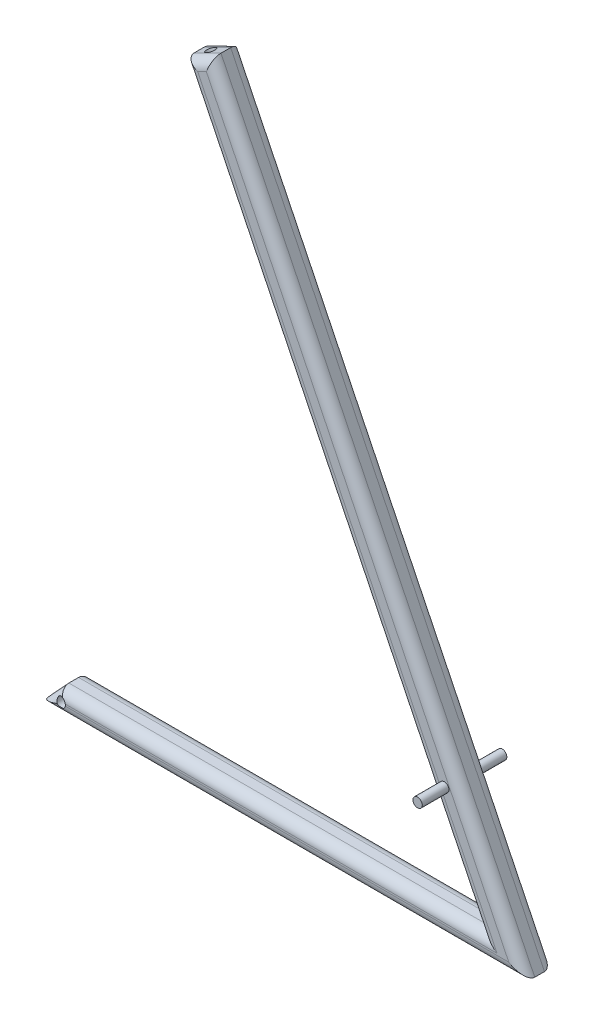
SolidWorks part; units mm, degrees
material "AA356.0-F"
ref_plane "Front Plane" through (0, 0, 0) normal (0, 0, 1) x (1, 0, 0)
ref_plane "Top Plane" through (0, 0, 0) normal (0, 1, 0) x (1, 0, 0)
ref_plane "Right Plane" through (0, 0, 0) normal (1, 0, 0) x (0, 0, -1)
sketch "Sketch1" plane through (0, 0, 0) normal (0, 0, 1) x (1, 0, 0)
  line L6 (-253.5187, -141.5797) -> (475.1092, -141.5797)
  line L7 (475.1092, -141.5797) -> (4.6879, 822.9269)
  line L8 (4.6879, 822.9269) -> (-35.3085, 803.4194)
  line L9 (-35.3085, 803.4194) -> (409.6382, -108.8566)
  line L10 (409.6382, -108.8566) -> (-223.3618, -108.8566)
  line L11 (-223.3618, -108.8566) -> (-253.5187, -141.5797)
  dimension "D1" = 64
  dimension "D2" = 728.6279
  dimension "D3" = 44.5
  dimension "D4" = 1015
  dimension "D5" = 633
  dimension "D6" = 44.5
extrude "Boss-Extrude1" add sketch "Sketch1" along normal blind 44.5
fillet "Fillet2" radius 15 12 edges at (93.1382, -108.8566, 44.5) (187.1649, 347.2814, 44.5) (-15.3103, 813.1732, 44.5) (239.8985, 340.6736, 44.5) (110.7952, -141.5797, 44.5) (-238.4402, -125.2181, 44.5) (110.7952, -141.5797, 0) (239.8985, 340.6736, 0) (-15.3103, 813.1732, 0) (187.1649, 347.2814, 0) (93.1382, -108.8566, 0) (-238.4402, -125.2181, 0)
sketch "Sketch2" plane through (-323.3368, 662.9386, 0) normal (-0.4384, 0.8988, 0) x (0.8988, 0.4384, 0)
  circle A0 centre (339.4702, -21.9136) radius 7
extrude "Cut-Extrude1" cut sketch "Sketch2" against normal blind 14
sketch "Sketch3" plane through (-66.5341, 61.3164, 0) normal (-0.7354, 0.6777, 0) x (0, 0, 1)
  circle A0 centre (22.3663, -255.5101) radius 7
extrude "Cut-Extrude2" cut sketch "Sketch3" against normal blind 14
sketch "Sketch4" plane through (0, -141.5797, 0) normal (0, -1, 0) x (-1, 0, 0)
  circle A0 centre (233.4195, -21.2015) radius 7
extrude "Cut-Extrude3" cut sketch "Sketch4" against normal blind 14
sketch "Sketch5" plane through (0, 0, 44.5) normal (0, 0, 1) x (1, 0, 0)
  circle A1 centre (-220.6491, -125.4271) radius 7
extrude "Cut-Extrude4" cut sketch "Sketch5" against normal through all
sketch "Sketch6" plane through (-66.5341, 61.3164, 0) normal (-0.7354, 0.6777, 0) x (0, 0, 1)
  line L1 (15, -231.4168) -> (29.5, -231.4168)
  line L2 (15, -231.4168) -> (15, -275.9168)
  line L3 (15, -275.9168) -> (29.5, -275.9168)
  line L4 (29.5, -231.4168) -> (29.5, -275.9168)
extrude "Cut-Extrude5" cut sketch "Sketch6" against normal through all
sketch "Sketch8" plane through (0, 0, 44.5) normal (0, 0, 1) x (1, 0, 0)
  line L0 (451.1042, -126.5797) -> (436.1934, -126.5797)
  line L1 (-213.7447, -126.5797) -> (451.1042, -126.5797) construction
  line L2 (436.1934, -126.5797) -> (433.6433, -123.8566)
  circle A0 centre (354.4285, 52.4167) radius 7
  point P8 (443.6488, -126.5797)
  line M6 (-15.251, 796.5131) -> (433.6433, -123.8566)
  dimension "D1" = 200
extrude "Boss-Extrude3" add sketch "Sketch8" along normal blind 40 contours A0 M6 | A0 M6
sketch "Sketch9" plane through (0, 0, 0) normal (0, 0, -1) x (-1, 0, 0)
  line L0 (-451.1042, -126.5797) -> (-435.0794, -126.5797)
  line L1 (-451.1042, -126.5797) -> (213.7447, -126.5797) construction
  line L2 (-435.0794, -126.5797) -> (-433.6433, -123.8566)
  circle A0 centre (-356.7688, 53.8318) radius 7
  point P7 (-443.0918, -126.5797)
  line M5 (2.2185, 802.8694) -> (-451.1042, -126.5797)
  dimension "D1" = 200
extrude "Boss-Extrude4" add sketch "Sketch9" along normal blind 40 contours A0 M5
